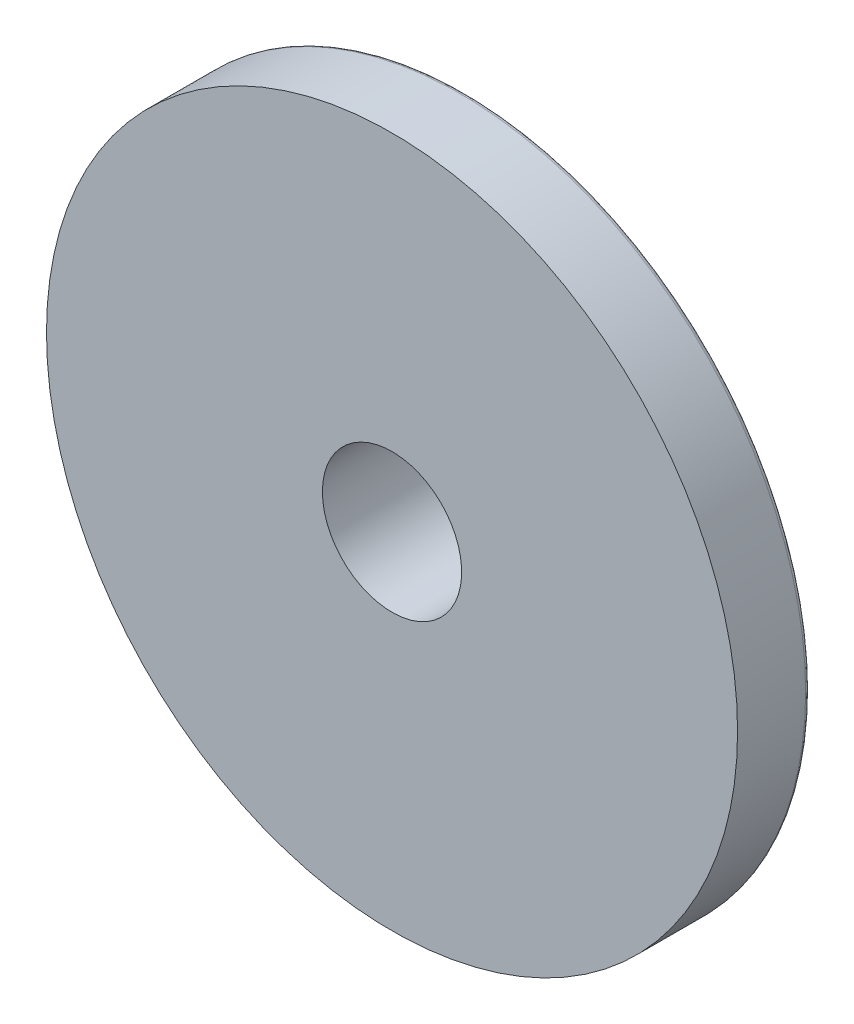
SolidWorks part; units mm, degrees
ref_plane "Front Plane" through (0, 0, 0) normal (0, 0, 1) x (1, 0, 0)
ref_plane "Top Plane" through (0, 0, 0) normal (0, 1, 0) x (1, 0, 0)
ref_plane "Right Plane" through (0, 0, 0) normal (1, 0, 0) x (0, 0, -1)
ref_plane "Plane_axle_y" through (0, -19.05, 0) normal (0, 1, 0) x (1, 0, 0)
sketch "Sk_flange_section" plane through (0, -19.05, 0) normal (0, 1, 0) x (1, 0, 0)
  line L0 (46.228, 7.9375) -> (76.9302, 7.9375)
  line L1 (76.9302, 7.9375) -> (76.9302, 15.5092)
  line L2 (46.228, 20.4445) -> (46.228, 7.9375)
  line L3 (38.481, 50.8) -> (38.481, -50.8) construction
  arc A0 (76.9302, 15.5092) -> (76.5843, 15.9917) centre (76.4197, 15.5084) ccw
  arc A1 (76.5843, 15.9917) -> (46.7387, 20.9534) centre (46.228, -74.3636) ccw
  arc A2 (46.7387, 20.9534) -> (46.228, 20.4445) centre (46.7354, 20.446) ccw
revolve "Rev_flange" add sketch "Sk_flange_section" angle 360 about L3
